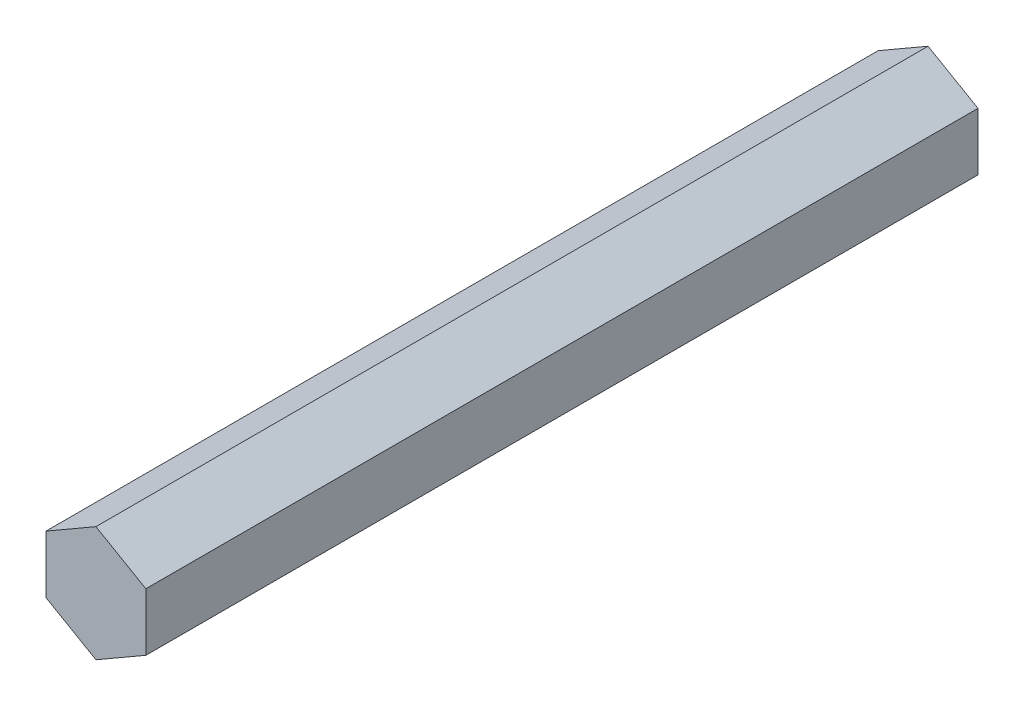
SolidWorks part; units mm, degrees
ref_plane "Front Plane" through (0, 0, 0) normal (0, 0, 1) x (1, 0, 0)
ref_plane "Top Plane" through (0, 0, 0) normal (0, 1, 0) x (1, 0, 0)
ref_plane "Right Plane" through (0, 0, 0) normal (1, 0, 0) x (0, 0, -1)
sketch "Sketch1" plane through (0, 0, 0) normal (0, 0, 1) x (1, 0, 0)
  line L1 (0, 5.4993) -> (-4.7625, 2.7496)
  line L2 (-4.7625, 2.7496) -> (-4.7625, -2.7496)
  line L3 (-4.7625, -2.7496) -> (0, -5.4993)
  line L4 (0, -5.4993) -> (4.7625, -2.7496)
  line L5 (4.7625, -2.7496) -> (4.7625, 2.7496)
  line L6 (4.7625, 2.7496) -> (0, 5.4993)
  circle A0 centre (0, 0) radius 4.7625 construction
  dimension "D1" = 9.525
extrude "Boss-Extrude1" add sketch "Sketch1" along normal blind 79.375
